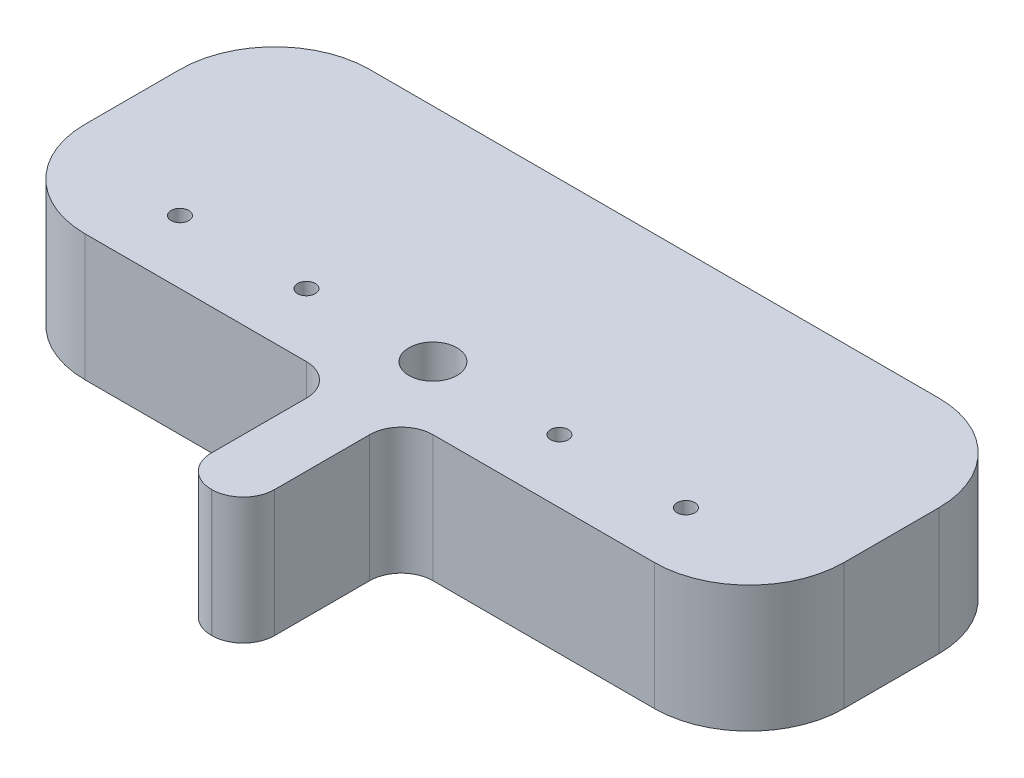
SolidWorks part; units mm, degrees
ref_plane "Front Plane" through (0, 0, 0) normal (0, 0, 1) x (1, 0, 0)
ref_plane "Top Plane" through (0, 0, 0) normal (0, 1, 0) x (1, 0, 0)
ref_plane "Right Plane" through (0, 0, 0) normal (1, 0, 0) x (0, 0, -1)
sketch "Sketch1" plane through (0, 0, 0) normal (0, 1, 0) x (1, 0, 0)
  line L0 (-12.2528, 4.0972) -> (9.9722, 4.0972)
  line L1 (-12.2528, 32.6722) -> (44.8972, 32.6722)
  line L2 (-21.7778, 23.1472) -> (-21.7778, 13.6222)
  line L3 (22.6722, 4.0972) -> (44.8972, 4.0972)
  line L4 (54.4222, 23.1472) -> (54.4222, 13.6222)
  line L7 (13.1472, 0.9222) -> (13.1472, -8.6282)
  line L8 (16.2968, -11.7778) -> (16.3476, -11.7778)
  line L9 (19.4972, 0.9222) -> (19.4972, -8.6282)
  arc A0 (13.1472, -8.6282) -> (16.2968, -11.7778) centre (16.2968, -8.6282) ccw
  arc A1 (-12.2528, 32.6722) -> (-21.7778, 23.1472) centre (-12.2528, 23.1472) ccw
  arc A2 (44.8972, 32.6722) -> (54.4222, 23.1472) centre (44.8972, 23.1472) cw
  arc A3 (16.3476, -11.7778) -> (19.4972, -8.6282) centre (16.3476, -8.6282) ccw
  circle A4 centre (16.3222, 10.4472) radius 2.413
  circle A5 centre (29.0222, 10.4472) radius 0.889
  circle A6 centre (3.6222, 10.4472) radius 0.889
  circle A7 centre (-9.0778, 10.4472) radius 0.889
  circle A8 centre (41.7222, 10.4472) radius 0.889
  arc A9 (19.4972, 0.9222) -> (22.6722, 4.0972) centre (22.6722, 0.9222) cw
  arc A10 (9.9722, 4.0972) -> (13.1472, 0.9222) centre (9.9722, 0.9222) cw
  arc A11 (44.8972, 4.0972) -> (54.4222, 13.6222) centre (44.8972, 13.6222) ccw
  arc A12 (-12.2528, 4.0972) -> (-21.7778, 13.6222) centre (-12.2528, 13.6222) cw
  point P6 (-21.7778, -11.7778)
  point P11 (54.4222, 32.6722)
  point P14 (54.4222, -11.7778)
  dimension "D3" = 34.925
  dimension "D4" = 4.826
  dimension "D7" = 1.778
  dimension "D8" = 1.778
  dimension "D5" = 1.778
  dimension "D9" = 1.778
  dimension "D12" = 3.1496
  dimension "D13" = 3.175
  dimension "D14" = 9.525
  dimension "D1" = 76.2
  dimension "D2" = 44.45
  dimension "D10" = 28.575
  dimension "D11" = 34.925
  dimension "D6" = 2
extrude "Boss-Extrude1" add sketch "Sketch1" along normal blind 12.7
